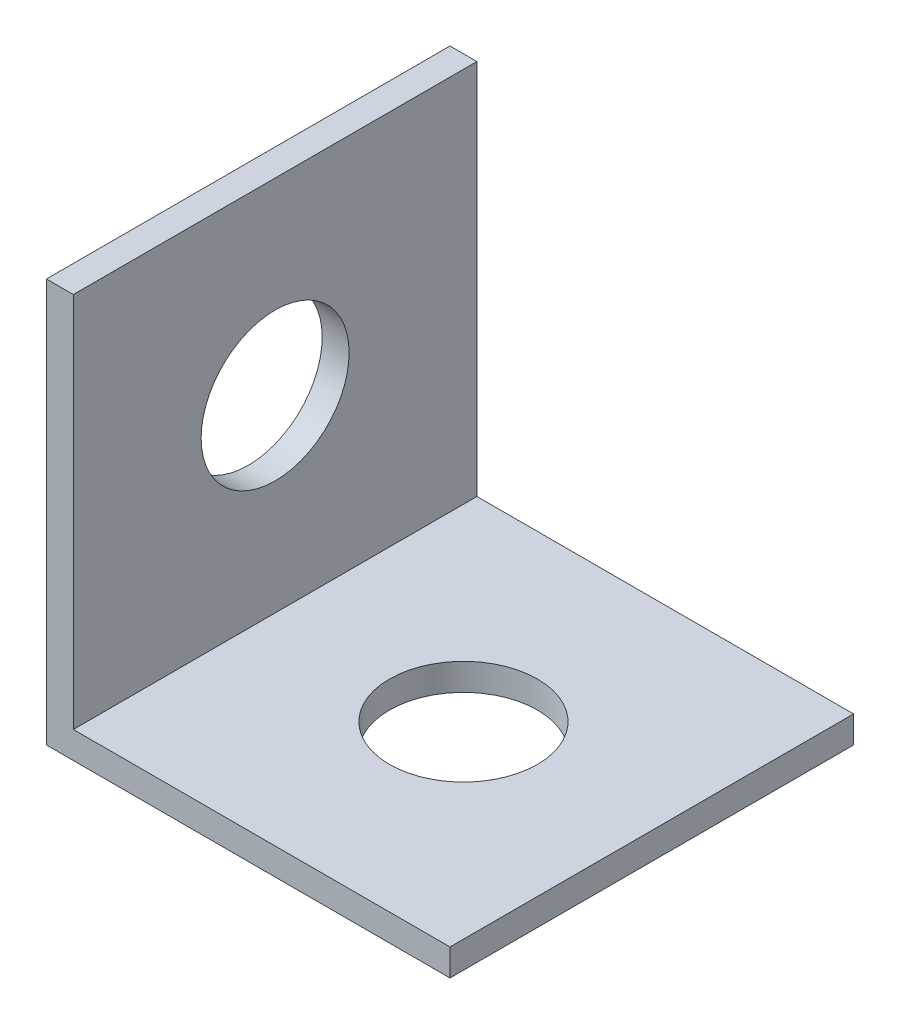
SolidWorks part; units mm, degrees
ref_plane "Front Plane" through (0, 0, 0) normal (0, 0, 1) x (1, 0, 0)
ref_plane "Top Plane" through (0, 0, 0) normal (0, 1, 0) x (1, 0, 0)
ref_plane "Right Plane" through (0, 0, 0) normal (1, 0, 0) x (0, 0, -1)
sketch "Sketch1" plane through (0, 0, 0) normal (0, 0, 1) x (1, 0, 0)
  line L0 (0, 0) -> (0, 15)
  line L1 (0, 15) -> (1, 15)
  line L2 (1, 15) -> (1, 1)
  line L3 (1, 1) -> (15, 1)
  line L4 (15, 1) -> (15, 0)
  line L5 (15, 0) -> (0, 0)
  dimension "D1" = 1
  dimension "D2" = 15
extrude "Boss-Extrude1" add sketch "Sketch1" along normal blind 15
sketch "Sketch2" plane through (0, 0, 0) normal (0, -1, 0) x (-1, 0, 0)
  line L0 (-8, 0) -> (-8, -15) construction
  line L1 (-15, 0) -> (-1, 0) construction
  line L2 (-15, -15) -> (-1, -15) construction
  line L3 (-8, -15) -> (-1, -7.5) construction
  line L4 (-1, -15) -> (-1, 0) construction
  line L5 (-1, -7.5) -> (-15, -7.5) construction
  line L6 (-15, -15) -> (-15, 0) construction
  circle A0 centre (-8, -7.5) radius 2.75
  dimension "D1" = 5.5
extrude "Cut-Extrude1" cut sketch "Sketch2" against normal blind 19.05
sketch "Sketch3" plane through (1, 0, 0) normal (1, 0, 0) x (0, 0, -1)
  line L0 (-15, 8) -> (0, 8) construction
  line L1 (-15, 1) -> (-15, 15) construction
  line L2 (0, 1) -> (0, 15) construction
  line L3 (0, 8) -> (-7.5, 15) construction
  line L4 (-15, 15) -> (0, 15) construction
  line L5 (-7.5, 15) -> (-7.5, 1) construction
  line L6 (-15, 1) -> (0, 1) construction
  circle A0 centre (-7.5, 8) radius 2.75
  dimension "D1" = 5.5
extrude "Cut-Extrude2" cut sketch "Sketch3" against normal through all
